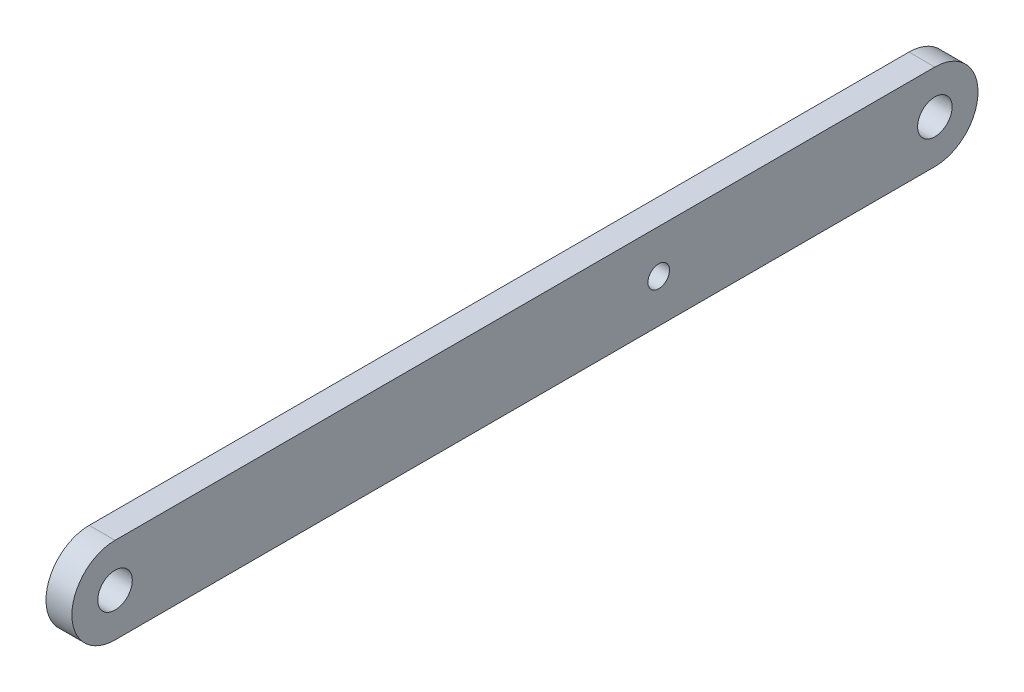
SolidWorks part; units mm, degrees
ref_plane "Front Plane" through (0, 0, 0) normal (0, 0, 1) x (1, 0, 0)
ref_plane "Top Plane" through (0, 0, 0) normal (0, 1, 0) x (1, 0, 0)
ref_plane "Right Plane" through (0, 0, 0) normal (1, 0, 0) x (0, 0, -1)
sketch "Sketch1" plane through (0, 0, 0) normal (1, 0, 0) x (0, 0, -1)
  line L0 (0, 0) -> (95, 0)
  line L1 (0, 10) -> (95, 10)
  line L2 (95, 5) -> (0, 5) construction
  arc A0 (0, 10) -> (0, 0) centre (0, 5) ccw
  arc A1 (95, 10) -> (95, 0) centre (95, 5) cw
  circle A2 centre (0, 5) radius 2
  circle A3 centre (95, 5) radius 2
  circle A4 centre (63, 5) radius 1.25
  dimension "D4" = 5
  dimension "D5" = 5
  dimension "D6" = 4
  dimension "D7" = 4
  dimension "D8" = 2.5
  dimension "D1" = 95
  dimension "D2" = 10
  dimension "D3" = 5
  dimension "D9" = 32
extrude "Boss-Extrude1" add sketch "Sketch1" along normal blind 3
